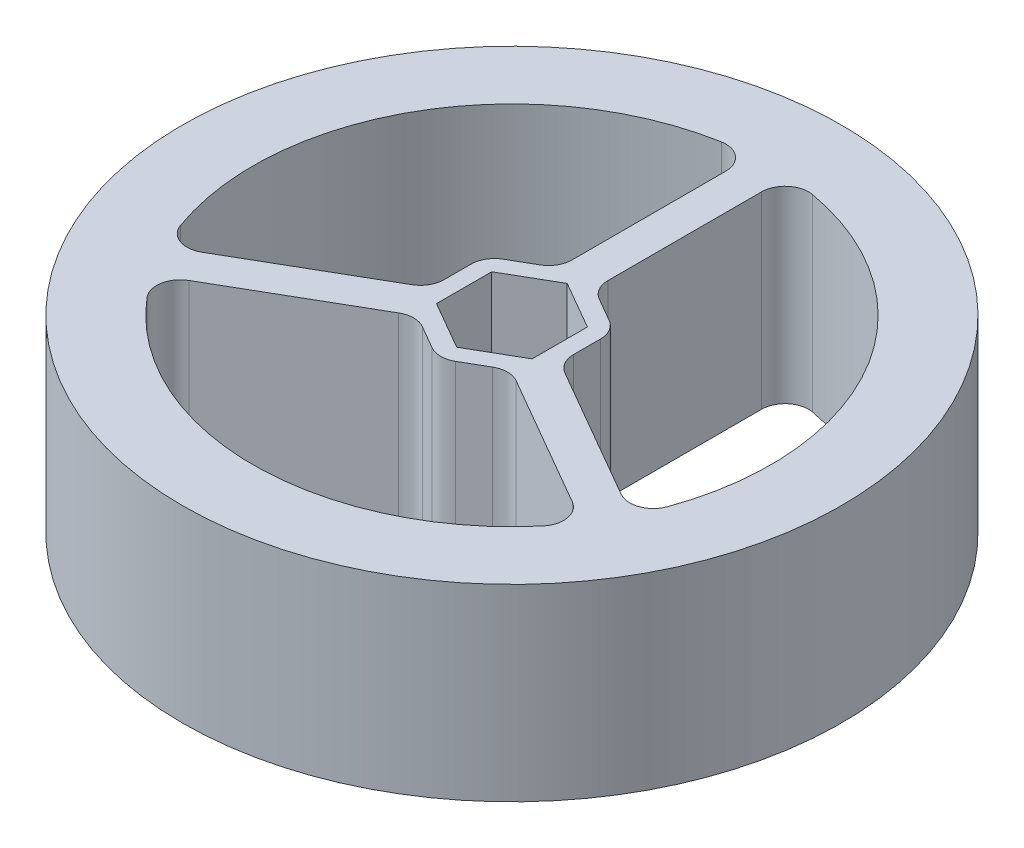
SolidWorks part; units mm, degrees
material "PET"
ref_plane "Front Plane" through (0, 0, 0) normal (0, 0, 1) x (1, 0, 0)
ref_plane "Top Plane" through (0, 0, 0) normal (0, 1, 0) x (1, 0, 0)
ref_plane "Right Plane" through (0, 0, 0) normal (1, 0, 0) x (0, 0, -1)
sketch "Sketch1" plane through (0, 0, 0) normal (0, 1, 0) x (1, 0, 0)
  line L0 (0, 0) -> (0, 34.925) construction
  line L1 (-2.413, 0) -> (-2.413, 34.925)
  line L2 (2.413, 0) -> (2.413, 34.925)
  line L3 (0, 0) -> (-30.2459, -17.4625) construction
  line L4 (1.2065, -2.0897) -> (-29.0394, -19.5522)
  line L5 (-1.2065, 2.0897) -> (-31.4524, -15.3728)
  line L6 (0, 0) -> (30.2459, -17.4625) construction
  line L7 (1.2065, 2.0897) -> (31.4524, -15.3728)
  line L8 (-1.2065, -2.0897) -> (29.0394, -19.5522)
  line L10 (-6.4516, 3.7248) -> (-6.4516, -3.7248)
  line L11 (-6.4516, -3.7248) -> (0, -7.4497)
  line L12 (0, -7.4497) -> (6.4516, -3.7248)
  line L13 (6.4516, -3.7248) -> (6.4516, 3.7248)
  line L14 (6.4516, 3.7248) -> (0, 7.4497)
  line L15 (0, 7.4497) -> (-6.4516, 3.7248)
  line L16 (-8.7376, 5.0447) -> (-8.7376, -5.0447)
  line L17 (-8.7376, -5.0447) -> (0, -10.0893)
  line L18 (0, -10.0893) -> (8.7376, -5.0447)
  line L19 (8.7376, -5.0447) -> (8.7376, 5.0447)
  line L20 (8.7376, 5.0447) -> (0, 10.0893)
  line L21 (0, 10.0893) -> (-8.7376, 5.0447)
  circle A0 centre (0, 0) radius 44.45
  circle A1 centre (0, 0) radius 34.925
  arc A4 (-2.413, 0) -> (2.413, 0) centre (0, 0) ccw
  arc A5 (2.413, 34.925) -> (-2.413, 34.925) centre (0, 34.925) ccw
  arc A6 (1.2065, -2.0897) -> (-1.2065, 2.0897) centre (0, 0) ccw
  arc A7 (-31.4524, -15.3728) -> (-29.0394, -19.5522) centre (-30.2459, -17.4625) ccw
  arc A8 (1.2065, 2.0897) -> (-1.2065, -2.0897) centre (0, 0) ccw
  arc A9 (29.0394, -19.5522) -> (31.4524, -15.3728) centre (30.2459, -17.4625) ccw
  circle A10 centre (0, 0) radius 6.4516 construction
  circle A11 centre (0, 0) radius 8.7376 construction
  point P7 (0, 17.4625)
  point P14 (-15.123, -8.7313)
  point P21 (15.123, -8.7313)
  dimension "D1" = 88.9
  dimension "D2" = 9.525
  dimension "D3" = 12.9032
  dimension "D4" = 2.286
  dimension "D5" = 2.413
  dimension "D6" = 120
extrude "Boss-Extrude1" add sketch "Sketch1" along normal blind 25.4
fillet "Fillet1" radius 3.175 15 edges at (2.413, 12.7, -34.8415) (-2.413, 12.7, -34.8415) (-31.3802, 12.7, 15.3311) (31.3802, 12.7, 15.3311) (28.9672, 12.7, 19.5105) (-28.9672, 12.7, 19.5105) (-8.7376, 12.7, 2.2584) (-8.7376, 12.7, -5.0447) (-2.413, 12.7, -8.6962) (2.413, 12.7, -8.6962) (8.7376, 12.7, -5.0447) (8.7376, 12.7, 2.2584) (6.3246, 12.7, 6.4378) (0, 12.7, 10.0893) (-6.3246, 12.7, 6.4378)
